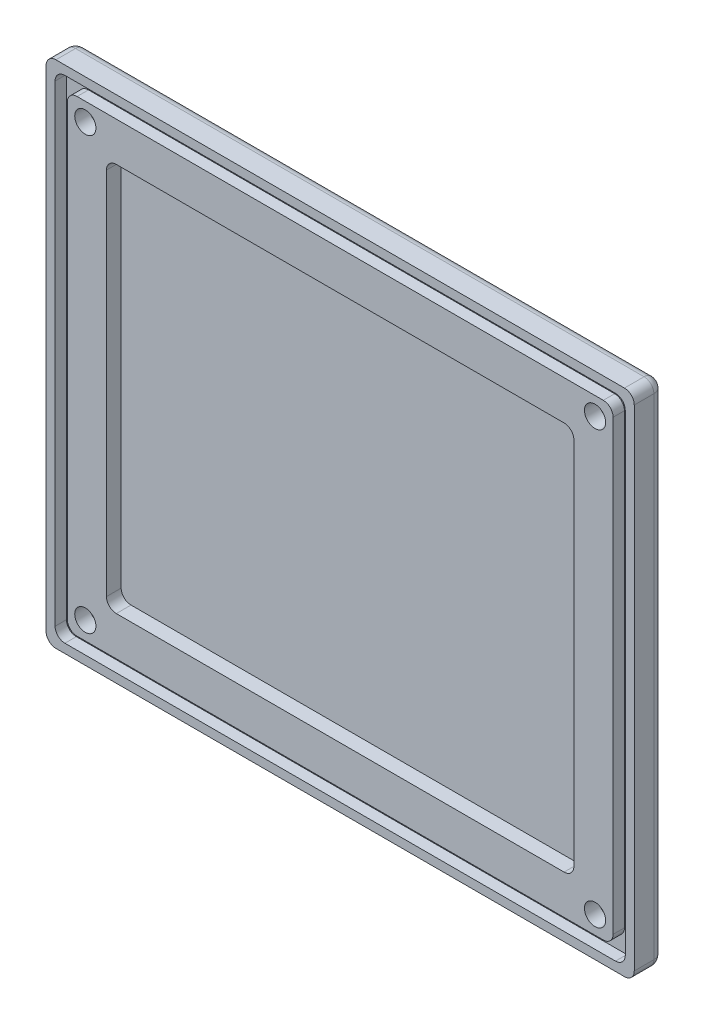
SolidWorks part; units mm, degrees
ref_plane "Front Plane" through (0, 0, 0) normal (0, 0, 1) x (1, 0, 0)
ref_plane "Top Plane" through (0, 0, 0) normal (0, 1, 0) x (1, 0, 0)
ref_plane "Right Plane" through (0, 0, 0) normal (1, 0, 0) x (0, 0, -1)
sketch "Sketch1" plane through (0, 0, 0) normal (0, 0, 1) x (1, 0, 0)
  line L1 (-47.625, -41.275) -> (47.625, -41.275)
  line L2 (-47.625, -41.275) -> (-47.625, 41.275)
  line L3 (-47.625, 41.275) -> (47.625, 41.275)
  line L4 (47.625, -41.275) -> (47.625, 41.275)
  line L5 (-47.625, -41.275) -> (47.625, 41.275) construction
  line L6 (-47.625, 41.275) -> (47.625, -41.275) construction
  point P0 (0, 0)
  dimension "D1" = 82.55
  dimension "D2" = 95.25
extrude "Boss-Extrude1" add sketch "Sketch1" along normal blind 4.7625
sketch "Sketch2" plane through (0, 0, 4.7625) normal (0, 0, 1) x (1, 0, 0)
  line L0 (-47.625, 41.275) -> (-47.625, -41.275) construction
  line L1 (-46.169, -39.819) -> (46.169, -39.819)
  line L2 (-46.169, -39.819) -> (-46.169, 39.819)
  line L3 (-46.169, 39.819) -> (46.169, 39.819)
  line L4 (46.169, -39.819) -> (46.169, 39.819)
  line L5 (-46.169, -39.819) -> (46.169, 39.819) construction
  line L6 (-46.169, 39.819) -> (46.169, -39.819) construction
  line L7 (47.625, 41.275) -> (-47.625, 41.275) construction
  line L8 (47.625, -41.275) -> (47.625, 41.275) construction
  line L9 (-44.196, -37.846) -> (44.196, -37.846)
  line L10 (-44.196, -37.846) -> (-44.196, 37.846)
  line L11 (-44.196, 37.846) -> (44.196, 37.846)
  line L12 (44.196, -37.846) -> (44.196, 37.846)
  line L13 (-44.196, -37.846) -> (44.196, 37.846) construction
  line L14 (-44.196, 37.846) -> (44.196, -37.846) construction
  point P0 (0, 0)
  point P10 (0, 0)
  dimension "D1" = 1.456
  dimension "D2" = 1.456
  dimension "D3" = 3.429
  dimension "D4" = 3.429
extrude "Cut-Extrude1" cut sketch "Sketch2" against normal blind 1.8415
fillet "Fillet1" radius 1.5875 8 edges at (46.169, 39.819, 3.8418) (44.196, 37.846, 3.8418) (44.196, -37.846, 3.8418) (46.169, -39.819, 3.8418) (-44.196, -37.846, 3.8418) (-46.169, -39.819, 3.8418) (-46.169, 39.819, 3.8418) (-44.196, 37.846, 3.8418)
fillet "Fillet2" radius 1.5875 8 edges at (0, 41.275, 0) (-47.625, 0, 0) (0, -41.275, 0) (47.625, 0, 0) (47.625, -41.275, 2.3813) (-47.625, -41.275, 2.3813) (-47.625, 41.275, 2.3813) (47.625, 41.275, 2.3813)
sketch "Sketch3" plane through (0, 0, 0) normal (0, 0, -1) x (-1, 0, 0)
  line L0 (-46.0375, 41.275) -> (46.0375, 41.275) construction
  line L1 (-47.625, -39.6875) -> (-47.625, 39.6875) construction
  circle A0 centre (-41.275, 34.925) radius 1.7145
  dimension "D1" = 3.429
  dimension "D2" = 6.35
  dimension "D3" = 6.35
extrude "Cut-Extrude2" cut sketch "Sketch3" against normal through all
sketch "Sketch4" plane through (0, 0, 0) normal (0, 0, -1) x (-1, 0, 0)
  circle A0 centre (-41.275, 34.925) radius 3.048
  dimension "D1" = 6.096
extrude "Cut-Extrude3" cut sketch "Sketch4" against normal blind 2.3813
mirror "Mirror1" about plane through (0, 0, 0) normal (1, 0, 0) of "Cut-Extrude3", "Cut-Extrude2" second plane through (0, 0, 0) second plane normal (0, 1, 0)
sketch "Sketch5" plane through (0, 0, 4.7625) normal (0, 0, 1) x (1, 0, 0)
  line L0 (44.196, -36.2585) -> (44.196, 36.2585) construction
  line L1 (-36.2585, -31.496) -> (36.2585, -31.496)
  line L2 (-37.846, -29.9085) -> (-37.846, 29.9085)
  line L3 (-36.2585, 31.496) -> (36.2585, 31.496)
  line L4 (37.846, -29.9085) -> (37.846, 29.9085)
  line L5 (-37.846, -31.496) -> (37.846, 31.496) construction
  line L6 (-37.846, 31.496) -> (37.846, -31.496) construction
  line L7 (42.6085, 37.846) -> (-42.6085, 37.846) construction
  arc A0 (36.2585, 31.496) -> (37.846, 29.9085) centre (36.2585, 29.9085) cw
  arc A1 (37.846, -29.9085) -> (36.2585, -31.496) centre (36.2585, -29.9085) cw
  arc A2 (-37.846, -29.9085) -> (-36.2585, -31.496) centre (-36.2585, -29.9085) ccw
  arc A3 (-36.2585, 31.496) -> (-37.846, 29.9085) centre (-36.2585, 29.9085) ccw
  point P0 (0, 0)
  dimension "D3" = 1.5875
  dimension "D1" = 6.35
  dimension "D2" = 6.35
extrude "Cut-Extrude4" cut sketch "Sketch5" against normal blind 2.3813
